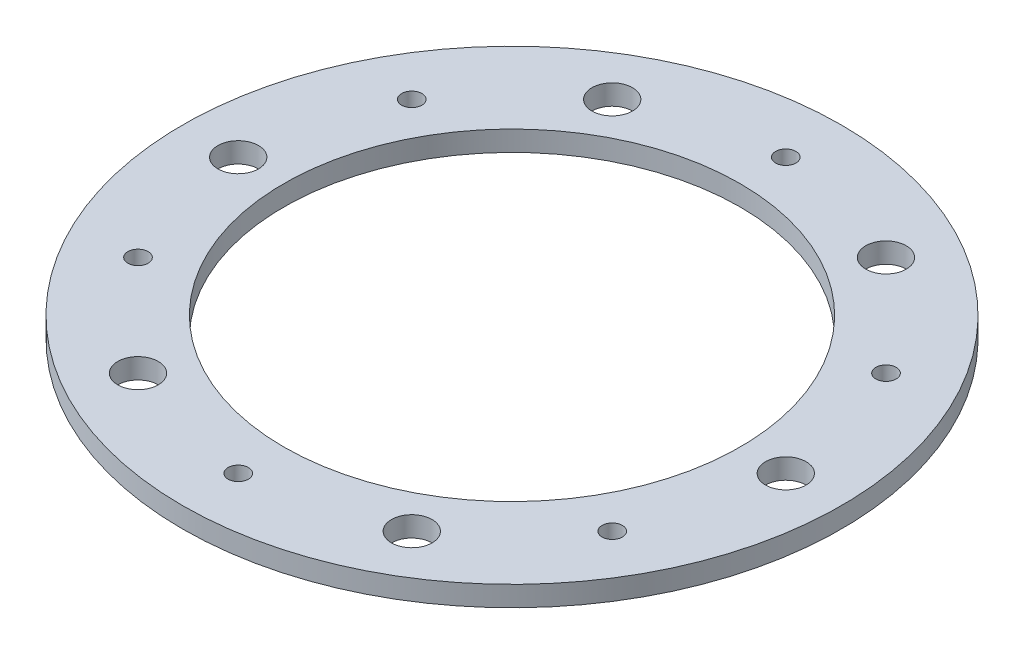
SolidWorks part; units mm, degrees
ref_plane "Front Plane" through (0, 0, 0) normal (0, 0, 1) x (1, 0, 0)
ref_plane "Top Plane" through (0, 0, 0) normal (0, 1, 0) x (1, 0, 0)
ref_plane "Right Plane" through (0, 0, 0) normal (1, 0, 0) x (0, 0, -1)
sketch "Sketch1" plane through (0, 0, 0) normal (0, 1, 0) x (1, 0, 0)
  circle A0 centre (0, 0) radius 32.5
  circle A1 centre (0, 0) radius 27 construction
  circle A2 centre (0, 27) radius 1
  circle A3 centre (23.3827, 13.5) radius 1
  circle A4 centre (23.3827, -13.5) radius 1
  circle A5 centre (0, -27) radius 1
  circle A6 centre (-23.3827, -13.5) radius 1
  circle A7 centre (-23.3827, 13.5) radius 1
  point P18 (0, 0)
  dimension "D1" = 65
  dimension "D2" = 54
  dimension "D3" = 2
  dimension "D4" = 6
extrude "Boss-Extrude1" add sketch "Sketch1" along normal blind 2
sketch "Sketch2" plane through (0, 2, 0) normal (0, 1, 0) x (1, 0, 0)
  line L0 (-13.5, 23.3827) -> (0, 0) construction
  line L1 (0, 0) -> (24.248, 0) construction
  circle A0 centre (0, 0) radius 22.5
  circle A1 centre (0, 0) radius 27 construction
  circle A2 centre (-13.5, 23.3827) radius 2
  circle A3 centre (13.5, 23.3827) radius 2
  circle A4 centre (27, 0) radius 2
  circle A5 centre (13.5, -23.3827) radius 2
  circle A6 centre (-13.5, -23.3827) radius 2
  circle A7 centre (-27, 0) radius 2
  point P19 (0, 0)
  dimension "D1" = 45
  dimension "D2" = 54
  dimension "D3" = 4
  dimension "D4" = 120
  dimension "D5" = 6
extrude "Cut-Extrude1" cut sketch "Sketch2" against normal through all
